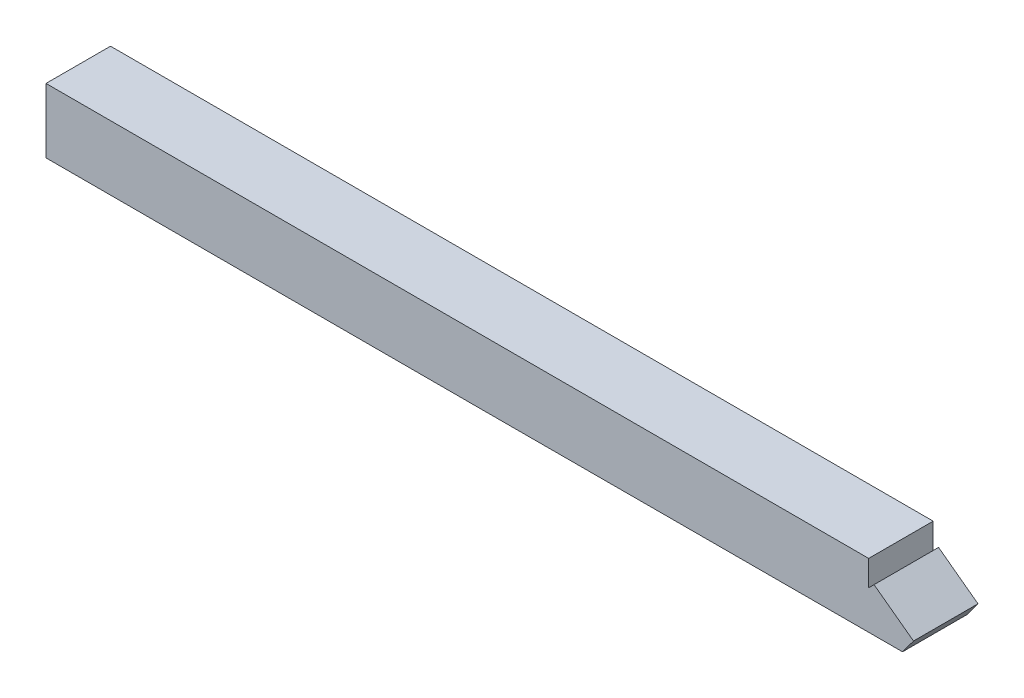
SolidWorks part; units mm, degrees
ref_plane "Front Plane" through (0, 0, 0) normal (0, 0, 1) x (1, 0, 0)
ref_plane "Top Plane" through (0, 0, 0) normal (0, 1, 0) x (1, 0, 0)
ref_plane "Right Plane" through (0, 0, 0) normal (1, 0, 0) x (0, 0, -1)
sketch "Sketch1" plane through (0, 0, 0) normal (0, 0, 1) x (1, 0, 0)
  line L0 (0, 0) -> (0, 1.5)
  line L2 (14.8868, 1.5141) -> (15.096, 1.7233)
  line L3 (15.096, 1.7233) -> (16.6243, 0.5945)
  line L4 (16.6243, 0.5945) -> (16.2, 0.02)
  line L5 (16.2, 0.02) -> (0, 0)
  line L6 (14.8868, 1.5141) -> (14.8868, 2.5)
  line L7 (14.8868, 2.5) -> (0, 2.5)
  line L8 (0, 2.5) -> (0, 1.5)
  dimension "D1" = 16.2
  dimension "D2" = 1
  dimension "D3" = 1.5
extrude "Boss-Extrude1" add sketch "Sketch1" along normal blind 2.5
sketch "Sketch2" plane through (0, 0, 0) normal (-1, 0, 0) x (0, 0, 1)
  line L4 (0, 2.5) -> (0, 0)
  line L5 (0, 0) -> (2.5, 0)
  line L6 (2.5, 0) -> (2.5, 2.5)
  line L7 (2.5, 2.5) -> (0, 2.5)
  line L8 (0, 2.5) -> (0, 0)
  line L9 (0, 0) -> (2.5, 0)
  line L10 (2.5, 0) -> (2.5, 2.5)
  line L11 (2.5, 2.5) -> (0, 2.5)
  dimension "D1" = 0
sketch "Sketch3" plane through (0, 0, 0) normal (-1, 0, 0) x (0, 0, 1)
  circle A0 centre (1.25, 1.25) radius 1
extrude "Cut-Extrude1" cut sketch "Sketch3" against normal blind 9.5
sketch "Sketch4" plane through (0, 0, 0) normal (-1, 0, 0) x (0, 0, 1)
  line L4 (0, 2.5) -> (0, 0)
  line L5 (0, 0) -> (2.5, 0)
  line L6 (2.5, 0) -> (2.5, 2.5)
  line L7 (2.5, 2.5) -> (0, 2.5)
  line L8 (0, 2.5) -> (0, 0)
  line L9 (0, 0) -> (2.5, 0)
  line L10 (2.5, 0) -> (2.5, 2.5)
  line L11 (2.5, 2.5) -> (0, 2.5)
  dimension "D1" = 0
extrude "Boss-Extrude3" add sketch "Sketch4" along normal blind 17
sketch "Sketch5" plane through (-17, 0, 0) normal (-1, 0, 0) x (0, 0, 1)
  circle A0 centre (1.25, 1.25) radius 1
extrude "Cut-Extrude2" cut sketch "Sketch5" against normal blind 9.5
